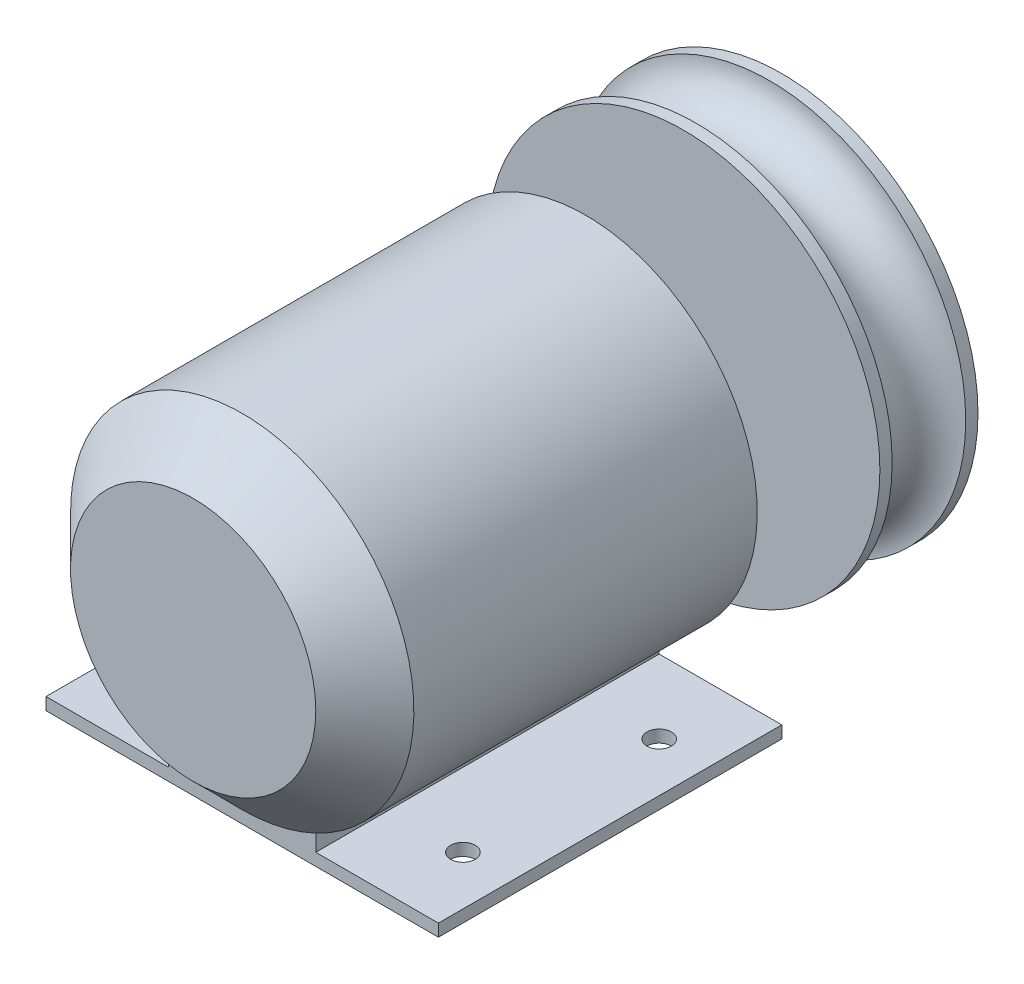
SolidWorks part; units mm, degrees
ref_plane "Front Plane" through (0, 0, 0) normal (0, 0, 1) x (1, 0, 0)
ref_plane "Top Plane" through (0, 0, 0) normal (0, 1, 0) x (1, 0, 0)
ref_plane "Right Plane" through (0, 0, 0) normal (1, 0, 0) x (0, 0, -1)
sketch "Sketch1" plane through (0, 0, 0) normal (0, 0, 1) x (1, 0, 0)
  circle A0 centre (0, 0) radius 44.45
  dimension "D1" = 88.9
extrude "Boss-Extrude1" add sketch "Sketch1" along normal blind 101.6
chamfer "Chamfer1" distance 12.7 angle 45 1 edges at (44.45, 0, 101.6)
sketch "Sketch2" plane through (0, 0, 0) normal (0, 0, -1) x (-1, 0, 0)
  circle A0 centre (0, 0) radius 3.175
  dimension "D1" = 6.35
extrude "Boss-Extrude2" add sketch "Sketch2" along normal blind 25.4
sketch "Sketch3" plane through (0, 0, 0) normal (1, 0, 0) x (0, 0, -1)
  line L0 (25.4, -3.175) -> (25.4, 3.175) construction
  line L1 (25.4, 0) -> (50.8, 0)
  line L2 (25.4, 0) -> (25.4, 50.8)
  line L3 (25.4, 50.8) -> (28.575, 50.8)
  line L4 (50.8, 0) -> (50.8, 50.8)
  line L5 (47.625, 50.8) -> (50.8, 50.8)
  arc A0 (28.575, 50.8) -> (47.625, 50.8) centre (38.1, 50.8) ccw
  dimension "D1" = 25.4
  dimension "D2" = 50.8
revolve "Revolve2" add sketch "Sketch3" angle 360 about L1
sketch "Sketch4" plane through (0, 0, -50.8) normal (0, 0, -1) x (-1, 0, 0)
  circle A0 centre (0, 0) radius 44.45
extrude "Cut-Extrude1" cut sketch "Sketch4" against normal blind 3.175
sketch "Sketch5" plane through (0, 0, 0) normal (0, 0, 1) x (1, 0, 0)
  line L1 (50.8, -44.45) -> (-50.8, -44.45)
  line L2 (50.8, -44.45) -> (50.8, -47.625)
  line L3 (50.8, -47.625) -> (-50.8, -47.625)
  line L4 (-50.8, -44.45) -> (-50.8, -47.625)
  circle A0 centre (0, 0) radius 44.45 construction
  dimension "D1" = 3.175
  dimension "D2" = 44.45
  dimension "D3" = 101.6
  dimension "D4" = 50.8
extrude "Boss-Extrude4" add sketch "Sketch5" along normal blind 88.9 separate body
sketch "Sketch6" plane through (0, 0, 88.9) normal (0, 0, 1) x (1, 0, 0)
  line L0 (50.8, -44.45) -> (-50.8, -44.45) construction
  line L1 (-19.05, -44.45) -> (19.05, -44.45)
  line L2 (-19.05, -44.45) -> (-19.05, -37.4399)
  line L3 (-19.05, -37.4399) -> (19.05, -37.4399)
  line L4 (19.05, -44.45) -> (19.05, -37.4399)
  dimension "D1" = 38.1
  dimension "D2" = 19.05
extrude "Boss-Extrude5" add sketch "Sketch6" against normal blind 88.9
sketch "Sketch7" plane through (0, -44.45, 0) normal (0, 1, 0) x (1, 0, 0)
  circle A0 centre (38.1, -19.05) radius 3.175
  circle A1 centre (38.1, -69.85) radius 3.175
  dimension "D1" = 6.35
  dimension "D2" = 6.35
  dimension "D3" = 19.05
  dimension "D4" = 19.05
  dimension "D5" = 12.7
  dimension "D6" = 12.7
extrude "Cut-Extrude2" cut sketch "Sketch7" against normal blind 88.9
sketch "Sketch8" plane through (0, -44.45, 0) normal (0, 1, 0) x (1, 0, 0)
  line L0 (-50.8, -88.9) -> (-50.8, 0) construction
  circle A0 centre (-38.1, -19.05) radius 3.175
  circle A1 centre (-38.1, -69.85) radius 3.175
  dimension "D1" = 6.35
  dimension "D2" = 6.35
  dimension "D3" = 19.05
  dimension "D4" = 19.05
  dimension "D5" = 12.7
  dimension "D6" = 12.7
extrude "Cut-Extrude3" cut sketch "Sketch8" against normal blind 88.9
